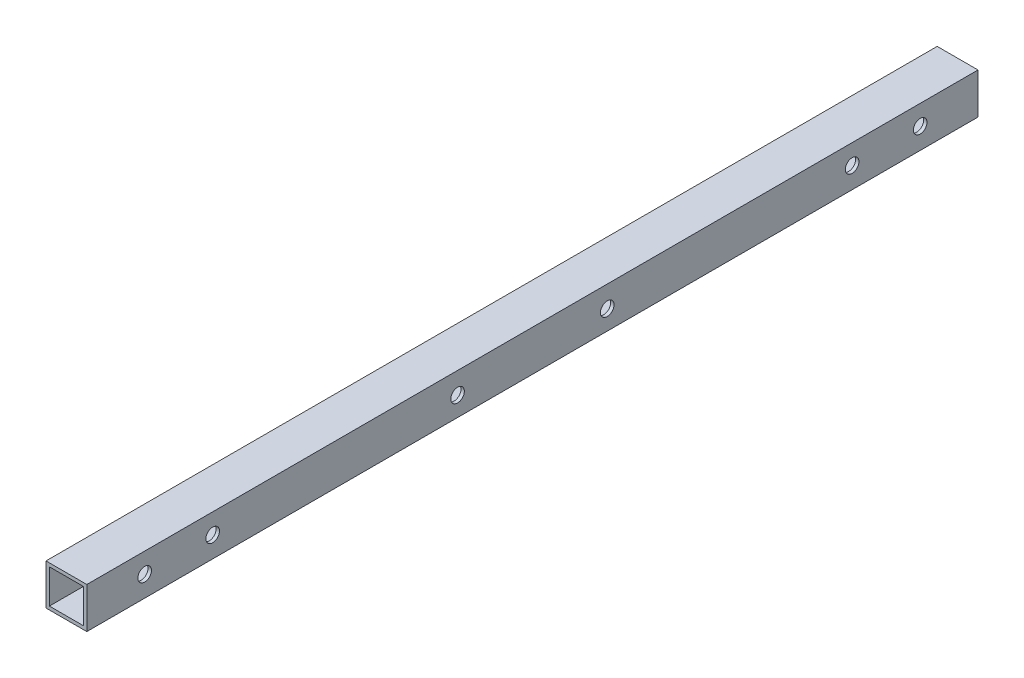
SolidWorks part; units mm, degrees
ref_plane "Front Plane" through (0, 0, 0) normal (0, 0, 1) x (1, 0, 0)
ref_plane "Top Plane" through (0, 0, 0) normal (0, 1, 0) x (1, 0, 0)
ref_plane "Right Plane" through (0, 0, 0) normal (1, 0, 0) x (0, 0, -1)
sketch "Sketch1" plane through (0, 0, 0) normal (0, 0, 1) x (1, 0, 0)
  line L0 (-15.875, 15.875) -> (15.875, 15.875)
  line L1 (-19.05, -19.05) -> (19.05, -19.05)
  line L2 (-19.05, -19.05) -> (-19.05, 19.05)
  line L3 (-19.05, 19.05) -> (19.05, 19.05)
  line L4 (19.05, -19.05) -> (19.05, 19.05)
  line L5 (-19.05, -19.05) -> (19.05, 19.05) construction
  line L6 (-19.05, 19.05) -> (19.05, -19.05) construction
  line L7 (15.875, -15.875) -> (15.875, 15.875)
  line L8 (-15.875, -15.875) -> (15.875, -15.875)
  line L9 (-15.875, -15.875) -> (-15.875, 15.875)
  point P0 (0, 0)
  dimension "D1" = 38.1
  dimension "D2" = 3.175
extrude "Boss-Extrude1" add sketch "Sketch1" along normal up to surface (831.85 mm away) from surface at -34.925
sketch "Sketch2" plane through (19.05, 0, 0) normal (1, 0, 0) x (0, 0, -1)
  circle A0 centre (-311.15, -0.9051) radius 6.35 construction
  circle A1 centre (-450.85, -0.9051) radius 6.35 construction
  circle A2 centre (-311.15, -0.9051) radius 6.35
  circle A3 centre (-450.85, -0.9051) radius 6.35
  circle A4 centre (-679.45, 0.3473) radius 6.35 construction
  circle A5 centre (-742.95, 0.3473) radius 6.35 construction
  circle A6 centre (-82.55, 0.5417) radius 6.35 construction
  circle A7 centre (-19.05, 0.5417) radius 6.35 construction
  circle A8 centre (-679.45, 0.3473) radius 6.35
  circle A9 centre (-742.95, 0.3473) radius 6.35
  circle A10 centre (-82.55, 0.5417) radius 6.35
  circle A11 centre (-19.05, 0.5417) radius 6.35
extrude "Cut-Extrude1" cut sketch "Sketch2" against normal through all
